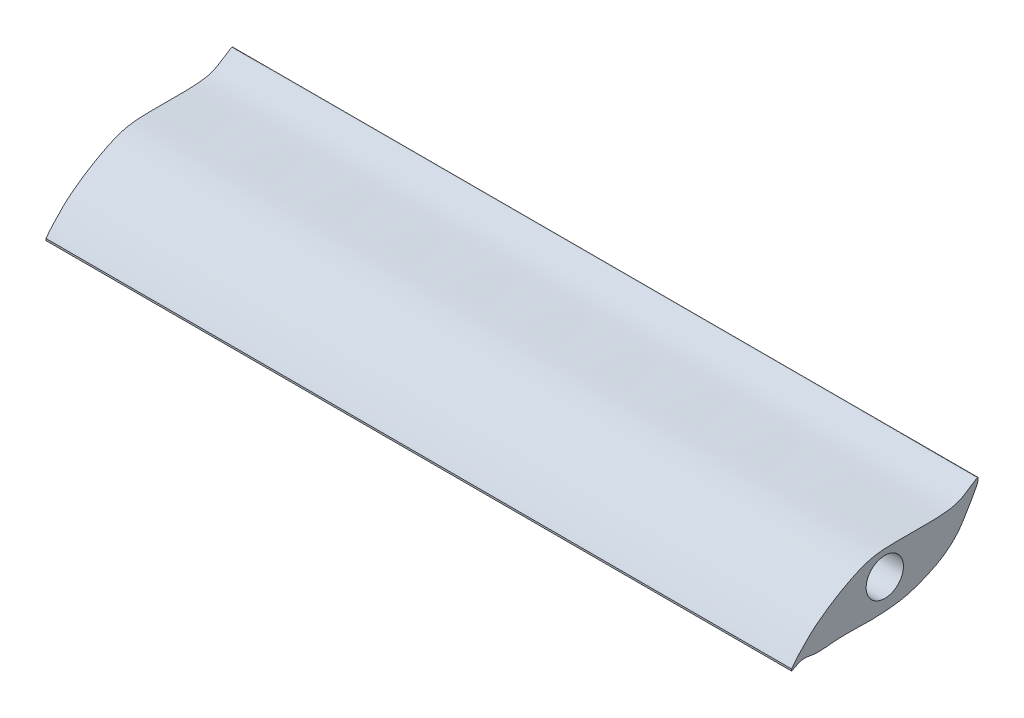
SolidWorks part; units mm, degrees
ref_plane "Front Plane" through (0, 0, 0) normal (0, 0, 1) x (1, 0, 0)
ref_plane "Top Plane" through (0, 0, 0) normal (0, 1, 0) x (1, 0, 0)
ref_plane "Right Plane" through (0, 0, 0) normal (1, 0, 0) x (0, 0, -1)
sketch "Sketch1" plane through (0, 0, 0) normal (0, 1, 0) x (1, 0, 0)
  line L1 (-50, 12.5) -> (50, 12.5)
  line L2 (-50, 12.5) -> (-50, -12.5)
  line L3 (-50, -12.5) -> (50, -12.5)
  line L4 (50, 12.5) -> (50, -12.5)
  line L5 (-50, 12.5) -> (50, -12.5) construction
  line L6 (-50, -12.5) -> (50, 12.5) construction
  point P0 (0, 0)
  dimension "D1" = 100
  dimension "D2" = 25
extrude "Boss-Extrude1" add sketch "Sketch1" along normal blind 10
sketch "Sketch2" plane through (50, 0, 0) normal (1, 0, 0) x (0, 0, -1)
  circle A0 centre (0, 4.6875) radius 2.5
  dimension "D1" = 5
extrude "Cut-Extrude1" cut sketch "Sketch2" against normal through all
sketch "Sketch3" plane through (50, 0, 0) normal (1, 0, 0) x (0, 0, -1)
  spline S0 degree 3 poles (-11.1191, 0.8535) (-13.554, -0.7887) (-10.565, 2.5746) (-9.0884, 3.8373) (-7.0311, 5.3201) (-4.7466, 6.6145) (-1.7752, 7.9848) (1.4056, 8.0266) (4.8106, 8.0226) (7.9132, 8.001) (10.4191, 8.5108) (13.5699, 11.1337) (11.0534, 6.8519) (9.9792, 5.0635) (8.1781, 3.2938) (5.8465, 2.0573) (2.9514, 0.9553) (-0.1924, 0.5985) (-3.3101, 0.5655) (-6.425, 0.7518) (-9.1686, 0.2172) (-11.1191, 0.8535) (-13.554, -0.7887) (-10.565, 2.5746) knots -0.108025 -0.051941 -0.022372 0 0.054297 0.090617 0.128983 0.179186 0.230327 0.296649 0.341806 0.410136 0.451575 0.490256 0.547998 0.591215 0.624531 0.673248 0.7295 0.78465 0.83734 0.891975 0.948059 0.977628 1 1.054297 1.090617 1.128983 only from (-12.5, 0) to (-12.5, 0)
extrude "Cut-Extrude2" cut sketch "Sketch3" against normal through all flip side to cut
